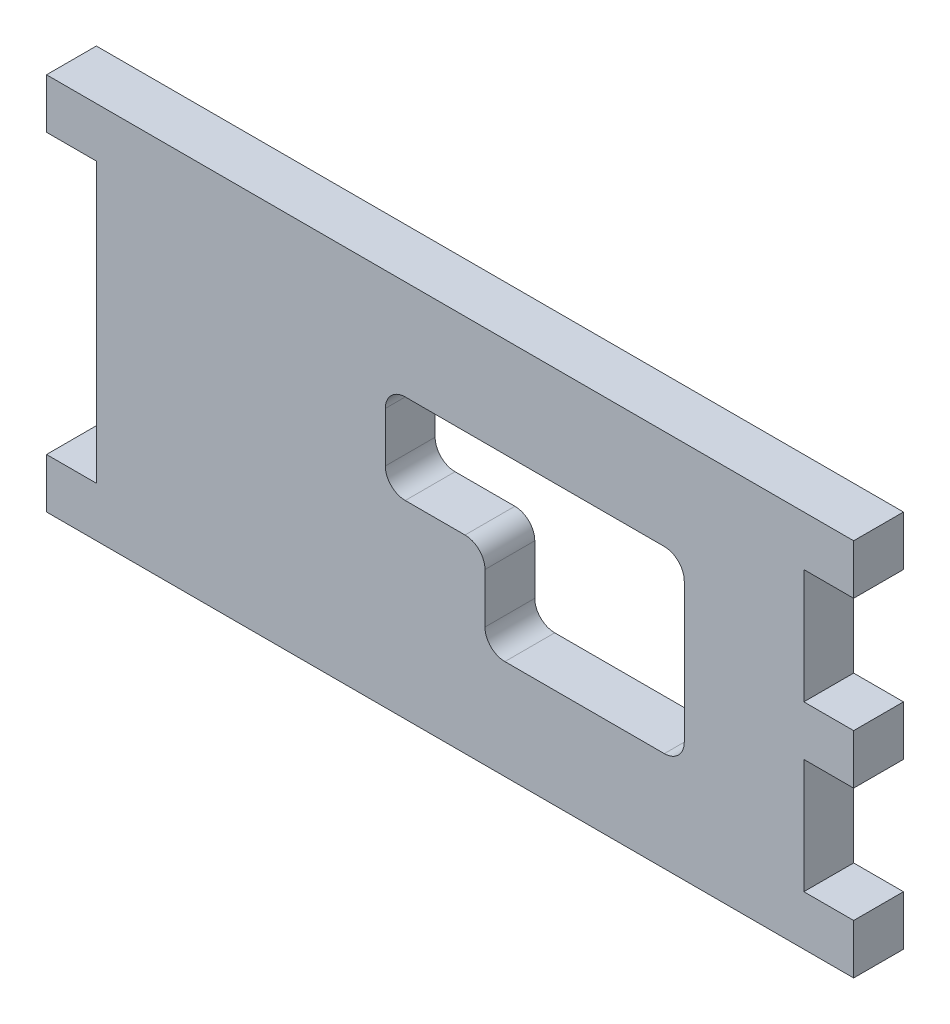
SolidWorks part; units mm, degrees
ref_plane "Plan de face" through (0, 0, 0) normal (0, 0, 1) x (1, 0, 0)
ref_plane "Plan de dessus" through (0, 0, 0) normal (0, 1, 0) x (1, 0, 0)
ref_plane "Plan de droite" through (0, 0, 0) normal (1, 0, 0) x (0, 0, -1)
sketch "Esquisse1" plane through (0, 0, 0) normal (0, 0, 1) x (1, 0, 0)
  line L1 (0, 0) -> (71, 0)
  line L3 (0, 38) -> (71, 38)
  line L4 (71, 5) -> (71, 16.5)
  line L5 (71, 38) -> (76, 38)
  line L7 (71, 33) -> (76, 33)
  line L8 (76, 38) -> (76, 33)
  line L9 (71, 0) -> (76, 0)
  line L11 (71, 5) -> (76, 5)
  line L12 (76, 0) -> (76, 5)
  line L13 (71, 21.5) -> (76, 21.5)
  line L15 (71, 16.5) -> (76, 16.5)
  line L16 (76, 21.5) -> (76, 16.5)
  line L17 (0, 38) -> (-5, 38)
  line L19 (0, 33) -> (-5, 33)
  line L20 (-5, 38) -> (-5, 33)
  line L21 (0, 5) -> (-5, 5)
  line L23 (0, 0) -> (-5, 0)
  line L24 (-5, 5) -> (-5, 0)
  line L25 (0, 5) -> (0, 33)
  line L26 (71, 21.5) -> (71, 33)
  line L27 (0, 38) -> (0, 33) construction
  line L28 (0, 5) -> (0, 0) construction
  line L29 (71, 16.5) -> (71, 21.5) construction
  line L30 (71, 33) -> (71, 38) construction
  line L31 (71, 5) -> (71, 0) construction
  line L32 (39, 28) -> (39, 19) construction
  line L33 (39, 28) -> (59, 28)
  line L34 (39, 19) -> (39, 10)
  line L35 (39, 10) -> (59, 10)
  line L36 (59, 28) -> (59, 10)
  line L37 (39, 28) -> (29, 28)
  line L39 (39, 19) -> (29, 19)
  line L40 (29, 28) -> (29, 19)
  dimension "D1" = 71
  dimension "D2" = 38
  dimension "D3" = 5
  dimension "D4" = 12
  dimension "D5" = 20
  dimension "D6" = 18
  dimension "D7" = 10
  dimension "D8" = 10
  dimension "D9" = 10
  dimension "D10" = 9
extrude "Boss.-Extru.1" add sketch "Esquisse1" along normal blind 5
fillet "Congé1" radius 2 6 edges at (59, 28, 2.5) (59, 10, 2.5) (39, 10, 2.5) (39, 19, 2.5) (29, 28, 2.5) (29, 19, 2.5)
